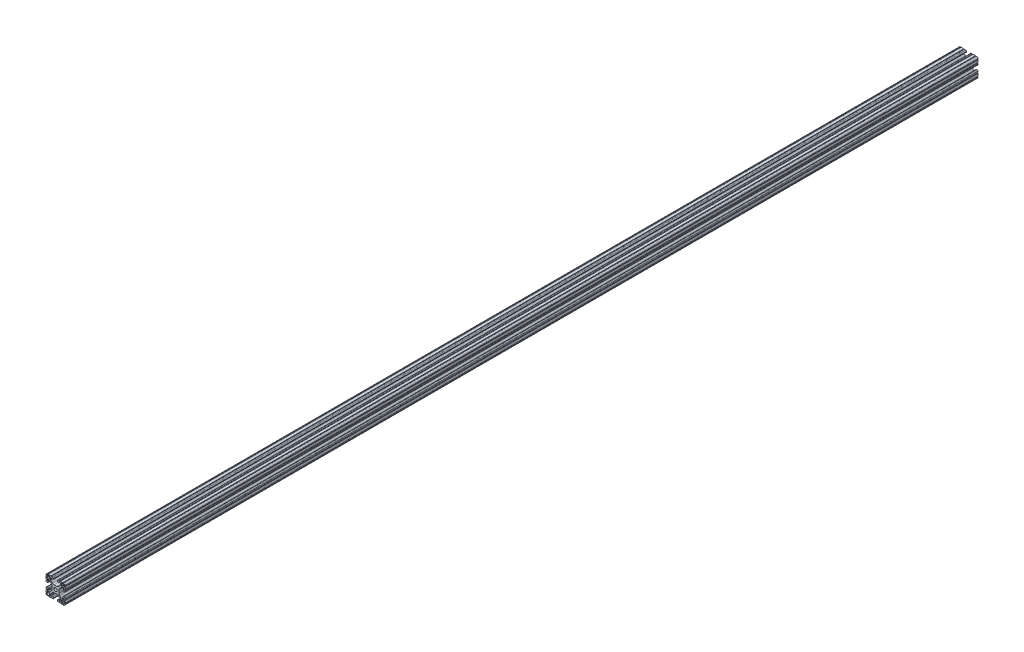
SolidWorks part; units mm, degrees
ref_plane "Front Plane" through (0, 0, 0) normal (0, 0, 1) x (1, 0, 0)
ref_plane "Top Plane" through (0, 0, 0) normal (0, 1, 0) x (1, 0, 0)
ref_plane "Right Plane" through (0, 0, 0) normal (1, 0, 0) x (0, 0, -1)
sketch "Sketch2" plane through (0, 0, 0) normal (0, 0, 1) x (1, 0, 0)
  line L0 (0, 19.05) -> (0, -19.05) construction
  line L1 (-19.05, 0) -> (19.05, 0) construction
  line L2 (4.064, -19.05) -> (19.05, -19.05) construction
  line L3 (19.05, -19.05) -> (19.05, -4.064) construction
  line L4 (4.064, -19.05) -> (4.064, -15.8768) construction
  line L5 (4.064, -15.8768) -> (13.7215, -15.8768) construction
  line L6 (13.7215, -15.8768) -> (4.7027, -6.858) construction
  line L7 (0, 0) -> (19.05, -19.05) construction
  line L8 (19.05, -4.064) -> (15.8768, -4.064) construction
  line L9 (15.8768, -4.064) -> (15.8768, -13.7215) construction
  line L10 (15.8768, -13.7215) -> (6.858, -4.7027) construction
  line L11 (11.3674, -9.2121) -> (9.2121, -11.3674) construction
  line L12 (10.287, -12.4423) -> (10.287, -15.8768) construction
  line L13 (15.7642, -19.0481) -> (4.064, -18.6395) construction
  line L14 (4.064, -18.6395) -> (4.2014, -14.7049) construction
  line L15 (4.2014, -14.7049) -> (6.858, -14.7977) construction
  line L16 (6.858, -14.7977) -> (6.858, -15.8768) construction
  line L17 (19.05, 4.064) -> (19.05, -4.064) construction
  line L18 (-19.05, -19.05) -> (19.05, -19.05) construction
  line L19 (-19.05, -19.05) -> (-19.05, 19.05) construction
  line L20 (-19.05, 19.05) -> (19.05, 19.05) construction
  line L21 (19.05, -19.05) -> (19.05, 19.05) construction
  line L22 (8.5725, -18.7969) -> (8.6004, -17.9973) construction
  line L23 (15.24, -19.0298) -> (15.2679, -18.2301) construction
  circle A0 centre (0, 0) radius 3.2639 construction
  arc A1 (18.1201, -18.1201) -> (15.7642, -19.0481) centre (15.875, -15.875) cw construction
  point P8 (0, -6.858)
  point P16 (10.2898, -10.2898)
  point P28 (11.8872, -11.8872)
  point P34 (8.5725, -18.7969)
  point P36 (15.24, -19.0298)
  point P38 (19.05, 0)
  dimension "D7" = 1.6002
  dimension "Center Hole Diameter" = 6.5278
  dimension "Corner Radius" = 3.175
  dimension "Slot Depth" = 12.192
  dimension "D1" = 3.048
  dimension "D3" = 2
  dimension "Flange Thickness" = 3.937
  dimension "D4" = 3.1732
  dimension "D2" = 20.574
  dimension "D5" = 13.716
  dimension "D6" = 7.1628
  dimension "D8" = 15.24
  dimension "D9" = 8.5725
  dimension "D10" = 0.8001
  dimension "Rail Height" = 38.1
  dimension "Rail Width" = 38.1
  dimension "T Slot Width" = 8.128
sketch "Sketch3" plane through (0, 0, 0) normal (1, 0, 0) x (0, 0, -1)
  line L0 (-914.4, 19.05) -> (914.4, 19.05) construction
  line L1 (-863.6, 0) -> (863.6, 0) construction
  dimension "Length" = 1828.8
  dimension "D1" = 50.8
sketch "Sketch4" plane through (0, 0, 0) normal (0, 0, 1) x (1, 0, 0)
  line L1 (6.858, -14.7977) -> (6.858, -15.8768) construction
  line L2 (11.8872, -12.2682) -> (11.8872, -16.9436)
  line L3 (12.2549, -17.3243) -> (14.4454, -17.4008)
  line L7 (12.2682, -11.8872) -> (16.9436, -11.8872)
  line L9 (17.3243, -12.2549) -> (17.4008, -14.4454)
  line L22 (0, 0) -> (19.05, -19.05) construction
  line L23 (15.7642, -19.0481) -> (5.5961, -18.693)
  line L24 (4.064, -17.1065) -> (4.064, -16.344)
  line L25 (5.7069, -14.7575) -> (6.4903, -14.7848)
  line L26 (6.858, -15.1656) -> (6.858, -15.6891)
  line L27 (7.2257, -16.0699) -> (9.4655, -16.1481)
  line L28 (10.287, -15.3549) -> (10.287, -12.771)
  line L29 (10.0545, -12.2098) -> (6.0939, -8.2492)
  line L30 (2.7353, -6.858) -> (0, -6.858)
  line L31 (13.7215, -15.8768) -> (4.7027, -6.858) construction
  line L32 (4.064, -19.05) -> (19.05, -19.05) construction
  line L33 (4.064, -19.05) -> (4.064, -15.8768) construction
  line L34 (0, 19.05) -> (0, -19.05) construction
  line L35 (0, -3.2639) -> (0, -6.858)
  line L36 (0, 0) -> (19.1669, -19.1669) construction
  line L46 (10.287, -12.4423) -> (10.287, -15.8768) construction
  line L47 (6.858, -2.7353) -> (6.858, 0)
  line L48 (12.2098, -10.0545) -> (8.2492, -6.0939)
  line L49 (15.3549, -10.287) -> (12.771, -10.287)
  line L50 (16.0699, -7.2257) -> (16.1481, -9.4655)
  line L51 (15.1656, -6.858) -> (15.6891, -6.858)
  line L52 (14.7575, -5.7069) -> (14.7848, -6.4903)
  line L53 (17.1065, -4.064) -> (16.344, -4.064)
  line L54 (19.0481, -15.7642) -> (18.693, -5.5961)
  line L55 (3.2639, 0) -> (6.858, 0)
  arc A1 (14.4454, -17.4008) -> (17.4008, -14.4454) centre (14.5451, -14.5451) ccw
  arc A10 (16.9436, -11.8872) -> (17.3243, -12.2549) centre (16.9436, -12.2682) cw
  arc A12 (19.0481, -15.7642) -> (15.7642, -19.0481) centre (15.875, -15.875) cw
  arc A13 (3.2639, 0) -> (0, -3.2639) centre (0, 0) cw
  circle A14 centre (0, 0) radius 3.2639 construction
  arc A16 (6.0939, -8.2492) -> (2.7353, -6.858) centre (2.7353, -11.6078) ccw
  arc A17 (5.5961, -18.693) -> (4.064, -17.1065) centre (5.6515, -17.1065) cw
  arc A18 (4.064, -16.344) -> (5.7069, -14.7575) centre (5.6515, -16.344) cw
  arc A19 (9.4655, -16.1481) -> (10.287, -15.3549) centre (9.4933, -15.3549) ccw
  arc A20 (10.287, -12.771) -> (10.0545, -12.2098) centre (9.4933, -12.771) ccw
  arc A21 (6.4903, -14.7848) -> (6.858, -15.1656) centre (6.477, -15.1656) cw
  arc A22 (6.858, -15.6891) -> (7.2257, -16.0699) centre (7.239, -15.6891) ccw
  arc A23 (15.6891, -6.858) -> (16.0699, -7.2257) centre (15.6891, -7.239) cw
  arc A24 (14.7848, -6.4903) -> (15.1656, -6.858) centre (15.1656, -6.477) ccw
  arc A25 (12.771, -10.287) -> (12.2098, -10.0545) centre (12.771, -9.4933) cw
  arc A26 (16.1481, -9.4655) -> (15.3549, -10.287) centre (15.3549, -9.4933) cw
  arc A27 (16.344, -4.064) -> (14.7575, -5.7069) centre (16.344, -5.6515) ccw
  arc A28 (18.693, -5.5961) -> (17.1065, -4.064) centre (17.1065, -5.6515) ccw
  arc A29 (8.2492, -6.0939) -> (6.858, -2.7353) centre (11.6078, -2.7353) cw
  arc A30 (15.7642, -19.0481) -> (18.1201, -18.1201) centre (15.875, -15.875) ccw construction
  arc A31 (11.8872, -12.2682) -> (12.2682, -11.8872) centre (12.2682, -12.2682) cw
  arc A32 (11.8872, -16.9436) -> (12.2549, -17.3243) centre (12.2682, -16.9436) ccw
  point P33 (4.064, -18.6395)
  point P42 (6.858, -4.7027)
  point P45 (4.7027, -6.858)
  point P76 (18.6395, -4.064)
  point P89 (11.8872, -11.8872)
  dimension "D2" = 4.7498
  dimension "D3" = 0.7937
  dimension "D5" = 0.381
  dimension "D6" = 1.5875
  dimension "D8" = 2.8575
  dimension "D1" = 2
  dimension "D4" = 2.6784
  dimension "D7" = 1.6002
extrude "Boss-Extrude1" add sketch "Sketch4" along normal mid plane 1828.8
sketch "Sketch8" plane through (0, 0, 0) normal (0, 0, 1) x (1, 0, 0)
  line L0 (7.6492, -18.7647) -> (9.4958, -18.8292)
  line L1 (15.7642, -19.0481) -> (4.064, -18.6395) construction
  line L2 (9.4958, -18.8292) -> (9.2789, -18.4213)
  line L3 (7.894, -18.3729) -> (7.6492, -18.7647)
  line L4 (8.5725, -18.7969) -> (8.6004, -17.9973) construction
  line L5 (14.3167, -18.9975) -> (16.1633, -19.062)
  line L7 (16.1633, -19.062) -> (15.9464, -18.6541)
  line L8 (14.5615, -18.6058) -> (14.3167, -18.9975)
  line L9 (15.24, -19.0298) -> (15.2679, -18.2301) construction
  line L10 (0, 0) -> (19.05, -19.05) construction
  line L11 (18.6058, -14.5615) -> (18.9975, -14.3167)
  line L12 (19.062, -16.1633) -> (18.6541, -15.9464)
  line L13 (18.9975, -14.3167) -> (19.062, -16.1633)
  line L14 (18.3729, -7.894) -> (18.7647, -7.6492)
  line L15 (18.8292, -9.4958) -> (18.4213, -9.2789)
  line L16 (18.7647, -7.6492) -> (18.8292, -9.4958)
  arc A0 (9.2789, -18.4213) -> (7.894, -18.3729) centre (8.5725, -18.7969) ccw
  arc A1 (15.9464, -18.6541) -> (14.5615, -18.6058) centre (15.24, -19.0298) ccw
  arc A2 (18.6541, -15.9464) -> (18.6058, -14.5615) centre (19.0298, -15.24) cw
  arc A3 (18.4213, -9.2789) -> (18.3729, -7.894) centre (18.7969, -8.5725) cw
  dimension "D1" = 60
extrude "Cut-Extrude2" cut sketch "Sketch8" against normal through all both and the other way through all
mirror "Mirror1" about plane through (0, 0, 0) normal (1, 0, 0) of bodies 142 134
mirror "Mirror2" about plane through (0, 0, 0) normal (0, 1, 0) of bodies 135
sketch "Sketch5" plane through (0, 0, 0) normal (0, 0, 1) x (1, 0, 0)
  line L0 (-6.0939, 8.2492) -> (-10.0545, 12.2098) construction
  line L1 (-10.1338, 12.508) -> (-10.1338, 12)
  line L2 (-9.9645, 11.8306) -> (-9.6506, 11.8306)
  line L3 (-9.6506, 11.8306) -> (-9.6506, 12.508)
  line L4 (-9.6506, 12.508) -> (-10.1338, 12.508)
  line L5 (-9.9046, 12.0598) -> (-9.9645, 12) construction
  circle A0 centre (-9.9046, 12.0598) radius 0.254 construction
  arc A1 (-10.287, 12.771) -> (-10.0545, 12.2098) centre (-9.4933, 12.771) ccw construction
  arc A2 (-10.1338, 12) -> (-9.9645, 11.8306) centre (-9.9645, 12) ccw
  dimension "D2" = 0.508
  dimension "D3" = 0.1693
  dimension "D1" = 0.7112
  dimension "D4" = 0.508
extrude "Cut-Extrude1" cut sketch "Sketch5" against normal through all both and the other way through all
ref_plane "Plane1" through (0, 19.05, 0) normal (0, 1, 0) x (-1, 0, 0)
ref_plane "Plane2" through (19.05, 0, 0) normal (1, 0, 0) x (0, 0, -1)
ref_plane "Plane3" through (0, -19.05, 0) normal (0, -1, 0) x (1, 0, 0)
ref_plane "Plane4" through (-19.05, 0, 0) normal (-1, 0, 0) x (0, 0, 1)
equation "\"D1@Boss-Extrude1\"=\"Length@Sketch3\""
equation "\"D6@Sketch4\"=\"Corner Radius@Sketch2\"/2"
equation "\"D3@Sketch4\"=\"D6@Sketch4\"/2"
equation "\"D4@Sketch2\"=\"Flange Thickness@Sketch2\"*.806"
equation "\"D7@Sketch4\"=\"D7@Sketch2\""
equation "\"D8@Sketch4\"=\"Corner Radius@Sketch2\"*.9"
equation "\"D3@Sketch5\"=\"D2@Sketch5\"/3"
equation "\"D4@Sketch5\"=\"D2@Sketch5\""
equation "\"D8@Sketch2\"=\"Rail Width@Sketch2\"*.4"
equation "\"D9@Sketch2\"=\"Rail Width@Sketch2\"*.225"
equation "\"D10@Sketch2\"=\"D7@Sketch2\"/2"
